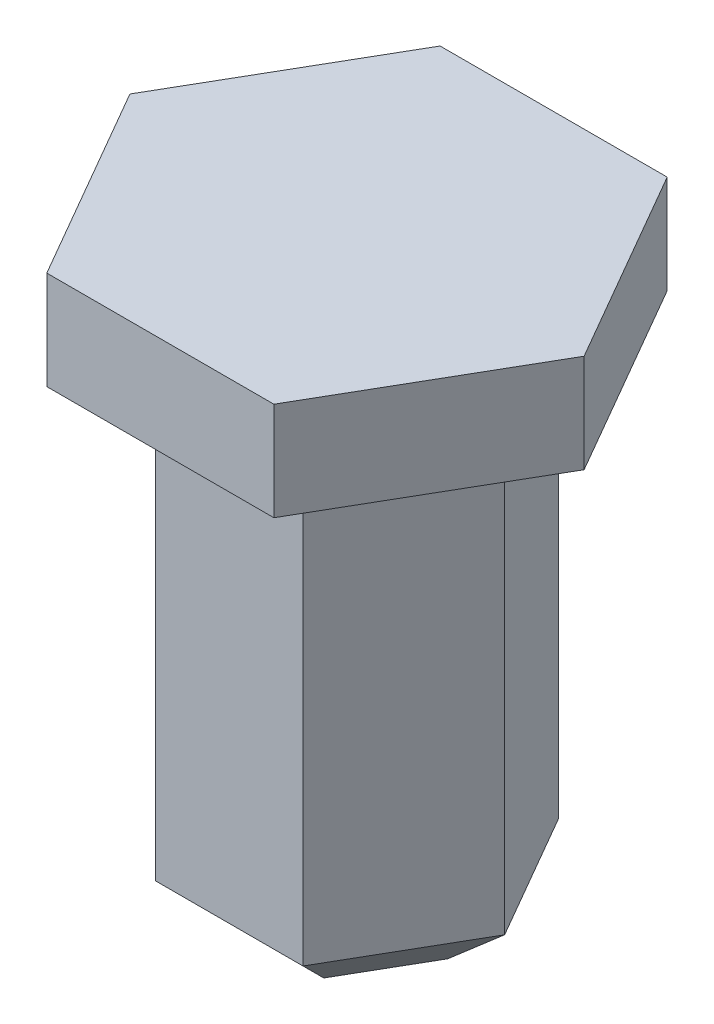
SolidWorks part; units mm, degrees
ref_plane "Front Plane" through (0, 0, 0) normal (0, 0, 1) x (1, 0, 0)
ref_plane "Top Plane" through (0, 0, 0) normal (0, 1, 0) x (1, 0, 0)
ref_plane "Right Plane" through (0, 0, 0) normal (1, 0, 0) x (0, 0, -1)
sketch "Sketch1" plane through (0, 0, 0) normal (0, 1, 0) x (1, 0, 0)
  line L1 (1.5011, 0) -> (0.7506, 1.3)
  line L2 (0.7506, 1.3) -> (-0.7506, 1.3)
  line L3 (-0.7506, 1.3) -> (-1.5011, 0)
  line L4 (-1.5011, 0) -> (-0.7506, -1.3)
  line L5 (-0.7506, -1.3) -> (0.7506, -1.3)
  line L6 (0.7506, -1.3) -> (1.5011, 0)
  circle A0 centre (0, 0) radius 1.3 construction
  dimension "D1" = 2.6
extrude "Boss-Extrude1" add sketch "Sketch1" along normal blind 5
sketch "Sketch2" plane through (0, 5, 0) normal (0, 1, 0) x (1, 0, 0)
  line L1 (2.3094, 0) -> (1.1547, 2)
  line L2 (1.1547, 2) -> (-1.1547, 2)
  line L3 (-1.1547, 2) -> (-2.3094, 0)
  line L4 (-2.3094, 0) -> (-1.1547, -2)
  line L5 (-1.1547, -2) -> (1.1547, -2)
  line L6 (1.1547, -2) -> (2.3094, 0)
  circle A0 centre (0, 0) radius 2 construction
  dimension "D1" = 4
extrude "Boss-Extrude2" add sketch "Sketch2" along normal blind 1
chamfer "Chamfer1" distance 0.5 angle 45 6 edges at (1.1258, 0, -0.65) (0, 0, -1.3) (-1.1258, 0, -0.65) (-1.1258, 0, 0.65) (0, 0, 1.3) (1.1258, 0, 0.65)
